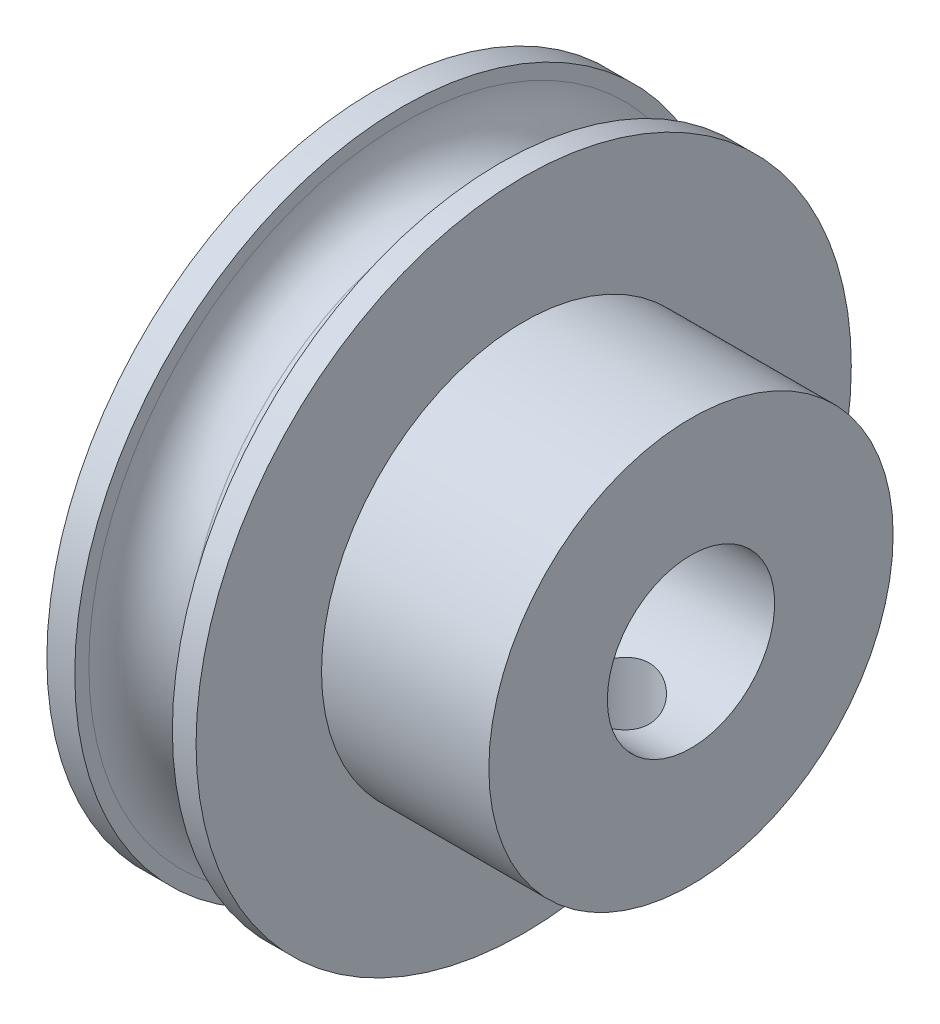
SolidWorks part; units mm, degrees
ref_plane "Спереди" through (0, 0, 0) normal (0, 0, 1) x (1, 0, 0)
ref_plane "Сверху" through (0, 0, 0) normal (0, 1, 0) x (1, 0, 0)
ref_plane "Справа" through (0, 0, 0) normal (1, 0, 0) x (0, 0, -1)
sketch "ы" plane through (0, 0, 0) normal (0, 0, 1) x (1, 0, 0)
  line L0 (0, 6) -> (22.7, 6)
  line L1 (22.7, 6) -> (22.7, 14.5)
  line L2 (22.7, 14.5) -> (10.7, 14.5)
  line L3 (10.7, 14.5) -> (10.7, 23.5)
  line L4 (10.7, 23.5) -> (9, 23.5)
  line L5 (9, 23.5) -> (9, 22.49)
  line L6 (5.51, 19) -> (5.49, 19)
  line L7 (2, 22.49) -> (2, 23.5)
  line L8 (2, 23.5) -> (0, 23.5)
  line L9 (0, 23.5) -> (0, 6)
  line L10 (0, 0) -> (31.5833, 0) construction
  arc A0 (5.49, 19) -> (2, 22.49) centre (5.49, 22.49) cw
  arc A1 (9, 22.49) -> (5.51, 19) centre (5.51, 22.49) cw
  point P13 (15.7917, 0)
  point P18 (2, 19)
  point P21 (9, 19)
  dimension "D5" = 3.49
  dimension "D1" = 6
  dimension "D2" = 14.5
  dimension "D3" = 23.5
  dimension "D4" = 12
  dimension "D6" = 1.7
  dimension "D7" = 2
  dimension "D8" = 7
  dimension "D9" = 4.5
revolve "Повернуть1" add sketch "ы" angle 360 about L10
sketch "Эскиз2" plane through (0, 0, 0) normal (0, 1, 0) x (1, 0, 0)
  line L0 (16.7, 14.5) -> (16.7, -22.5974) construction
  line L1 (22.7, 14.5) -> (10.7, 14.5) construction
  circle A0 centre (16.7, 0) radius 3
  dimension "D1" = 6
extrude "Вырез-Вытянуть1" cut sketch "Эскиз2" against normal up to next
